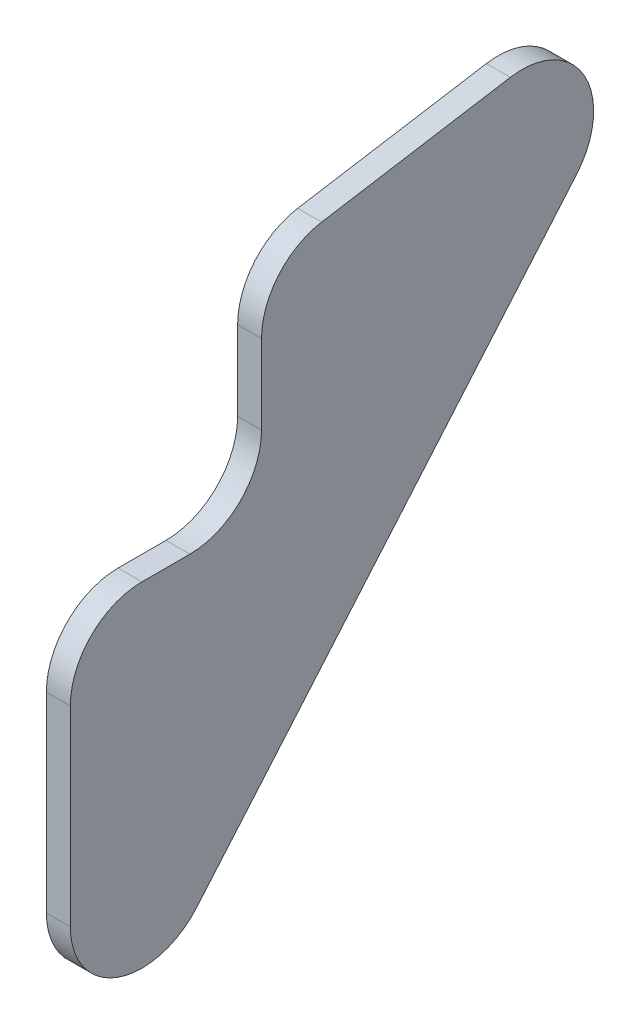
SolidWorks part; units mm, degrees
ref_plane "Front Plane" through (0, 0, 0) normal (0, 0, 1) x (1, 0, 0)
ref_plane "Top Plane" through (0, 0, 0) normal (0, 1, 0) x (1, 0, 0)
ref_plane "Right Plane" through (0, 0, 0) normal (1, 0, 0) x (0, 0, -1)
sketch "Sketch1" plane through (0, 0, 0) normal (1, 0, 0) x (0, 0, -1)
  line L0 (-1321.232, 253.0191) -> (-1270.7683, 312.1127) construction
  line L1 (-1304.62, 323.5779) -> (-1279.5563, 327.6971) construction
  line L2 (-1312.6003, 314.179) -> (-1312.6003, 294.1296) construction
  line L3 (-1312.6003, 294.1296) -> (-1328.4753, 294.1296) construction
  line L4 (-1338.0003, 259.2046) -> (-1338.0003, 284.6046) construction
  line L5 (-1321.232, 253.0191) -> (-1270.7683, 312.1127)
  line L6 (-1304.62, 323.5779) -> (-1279.5563, 327.6971)
  line L7 (-1312.6003, 314.179) -> (-1312.6003, 294.1296)
  line L8 (-1312.6003, 294.1296) -> (-1328.4753, 294.1296)
  line L9 (-1338.0003, 259.2046) -> (-1338.0003, 284.6046)
  circle A0 centre (-1278.0116, 318.2982) radius 9.525 construction
  circle A1 centre (-1303.0753, 314.179) radius 9.525 construction
  circle A2 centre (-1328.4753, 259.2046) radius 9.525 construction
  circle A3 centre (-1328.4753, 284.6046) radius 9.525 construction
  arc A4 (-1270.7683, 312.1127) -> (-1279.5563, 327.6971) centre (-1278.0116, 318.2982) ccw
  arc A5 (-1304.62, 323.5779) -> (-1312.6003, 314.179) centre (-1303.0753, 314.179) ccw
  arc A6 (-1338.0003, 259.2046) -> (-1321.232, 253.0191) centre (-1328.4753, 259.2046) ccw
  arc A7 (-1328.4753, 294.1296) -> (-1338.0003, 284.6046) centre (-1328.4753, 284.6046) ccw
extrude "Boss-Extrude1" add sketch "Sketch1" against normal up to vertex from vertex
fillet "Fillet1" radius 9.525 1 edges at (68.0086, 294.1296, 1312.6003)
